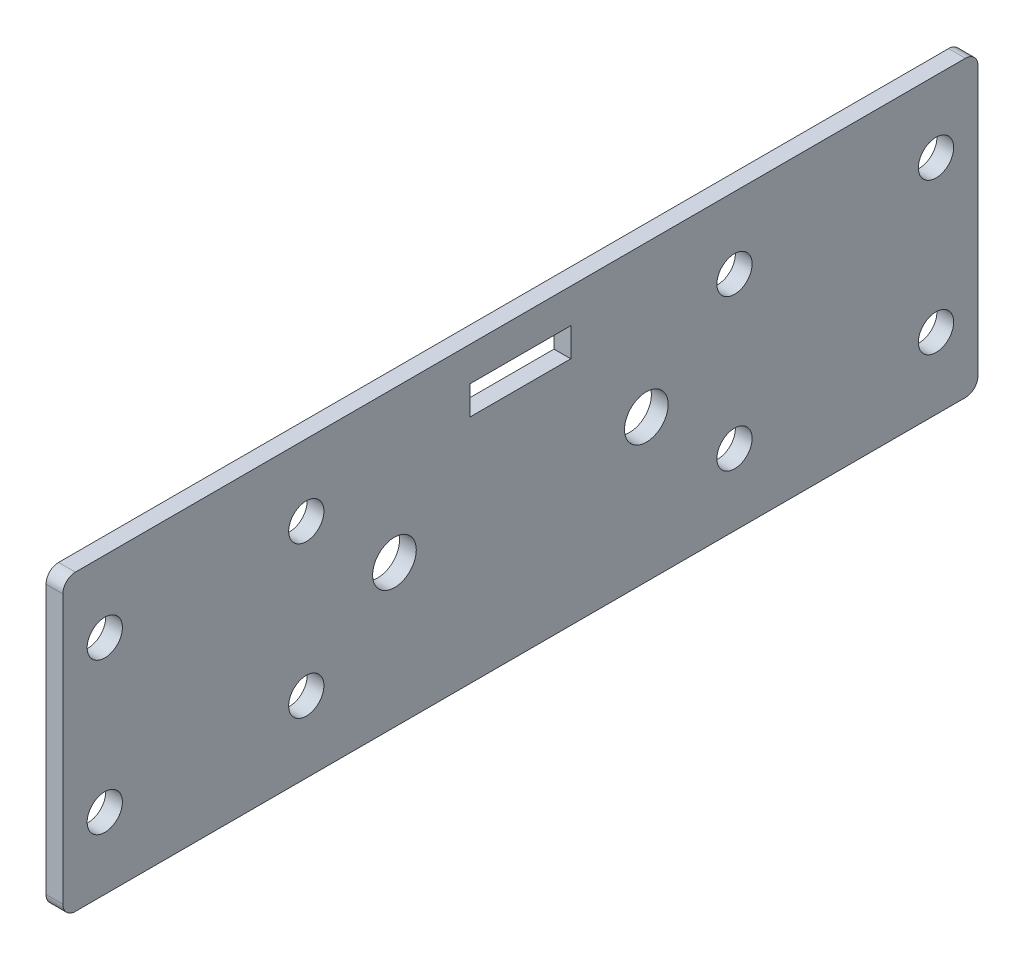
SolidWorks part; units mm, degrees
ref_plane "Front Plane" through (0, 0, 0) normal (0, 0, 1) x (1, 0, 0)
ref_plane "Top Plane" through (0, 0, 0) normal (0, 1, 0) x (1, 0, 0)
ref_plane "Right Plane" through (0, 0, 0) normal (1, 0, 0) x (0, 0, -1)
sketch "Sketch1" plane through (0, 0, 0) normal (1, 0, 0) x (0, 0, -1)
  line L0 (104, 0) -> (104, -35) construction
  line L1 (0, 0) -> (109, 0)
  line L2 (0, 0) -> (0, -35)
  line L3 (0, -35) -> (109, -35)
  line L4 (109, 0) -> (109, -35)
  line L5 (109, -17.5) -> (0, -17.5) construction
  line L6 (92, 0) -> (92, -35) construction
  line L7 (54.5, 0) -> (54.5, -35) construction
  line L8 (17, 0) -> (17, -35) construction
  line L9 (28.957, -18) -> (87.901, -18) construction
  line L10 (48.5, -4.08) -> (60.5, -4.08)
  line L11 (48.5, -4.08) -> (48.5, -7.5)
  line L12 (48.5, -7.5) -> (60.5, -7.5)
  line L13 (60.5, -4.08) -> (60.5, -7.5)
  line L14 (48.5, -4.08) -> (60.5, -7.5) construction
  line L15 (48.5, -7.5) -> (60.5, -4.08) construction
  circle A0 centre (104, -8.5) radius 2.1
  circle A1 centre (104, -26.5) radius 2.1
  circle A2 centre (80, -26.5) radius 2.1
  circle A3 centre (80, -8.5) radius 2.1
  circle A4 centre (5, -26.5) radius 2.1
  circle A5 centre (5, -8.5) radius 2.1
  circle A6 centre (29, -26.5) radius 2.1
  circle A7 centre (29, -8.5) radius 2.1
  circle A8 centre (39.5, -18) radius 2.6
  circle A9 centre (69.5, -18) radius 2.6
  point P31 (54.5, -5.79)
  dimension "D3" = 12
  dimension "D4" = 4.2
  dimension "D6" = 18
  dimension "D7" = 12
  dimension "D10" = 5.2
  dimension "D11" = 30
  dimension "D1" = 75
  dimension "D2" = 35
  dimension "D5" = 17
  dimension "D8" = 3.42
  dimension "D9" = 10.5
  dimension "D12" = 18
extrude "Boss-Extrude1" add sketch "Sketch1" along normal blind 2
fillet "Fillet1" radius 1.5 4 edges at (1, 0, -109) (1, -35, -109) (1, -35, 0) (1, 0, 0)
